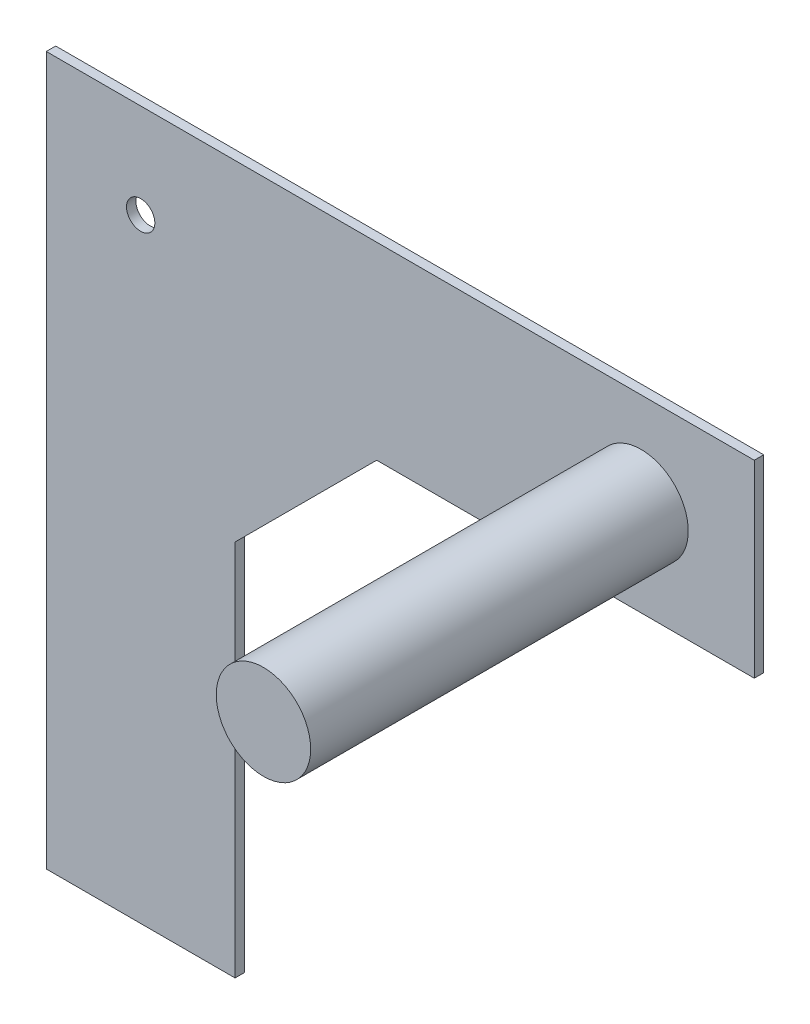
SolidWorks part; units mm, degrees
ref_plane "Front Plane" through (0, 0, 0) normal (0, 0, 1) x (1, 0, 0)
ref_plane "Top Plane" through (0, 0, 0) normal (0, 1, 0) x (1, 0, 0)
ref_plane "Right Plane" through (0, 0, 0) normal (1, 0, 0) x (0, 0, -1)
sketch "Sketch1" plane through (0, 0, 0) normal (0, 0, 1) x (1, 0, 0)
  line L0 (-20, 35) -> (-20, -40)
  line L1 (-20, -40) -> (0, -40)
  line L2 (0, -40) -> (0, 0)
  line L3 (-20, 35) -> (55, 35)
  line L4 (55, 35) -> (55, 15)
  line L5 (55, 15) -> (15, 15)
  line L6 (15, 15) -> (0, 0)
  dimension "D1" = 75
  dimension "D2" = 20
  dimension "D3" = 40
extrude "Boss-Extrude1" add sketch "Sketch1" along normal blind 1
sketch "Sketch4" plane through (0, 0, 1) normal (0, 0, 1) x (1, 0, 0)
  line L0 (-10, -40) -> (-10, 35) construction
  line L1 (-20, -40) -> (0, -40) construction
  line L2 (55, 35) -> (-20, 35) construction
  line L3 (43.821, 35) -> (43.821, 15) construction
  line L4 (15, 15) -> (55, 15) construction
  circle A0 centre (-10, 25.0001) radius 1.5
  point P6 (-10, 25.0001)
  dimension "D1" = 3
extrude "Cut-Extrude5" cut sketch "Sketch4" against normal blind 1
sketch "Sketch5" plane through (0, 0, 1) normal (0, 0, 1) x (1, 0, 0)
  line L0 (43.007, 35) -> (43.007, 15) construction
  line L1 (55, 35) -> (-20, 35) construction
  line L2 (15, 15) -> (55, 15) construction
  circle A0 centre (43.007, 25) radius 5
  dimension "D1" = 10
extrude "Boss-Extrude2" add sketch "Sketch5" along normal blind 40
